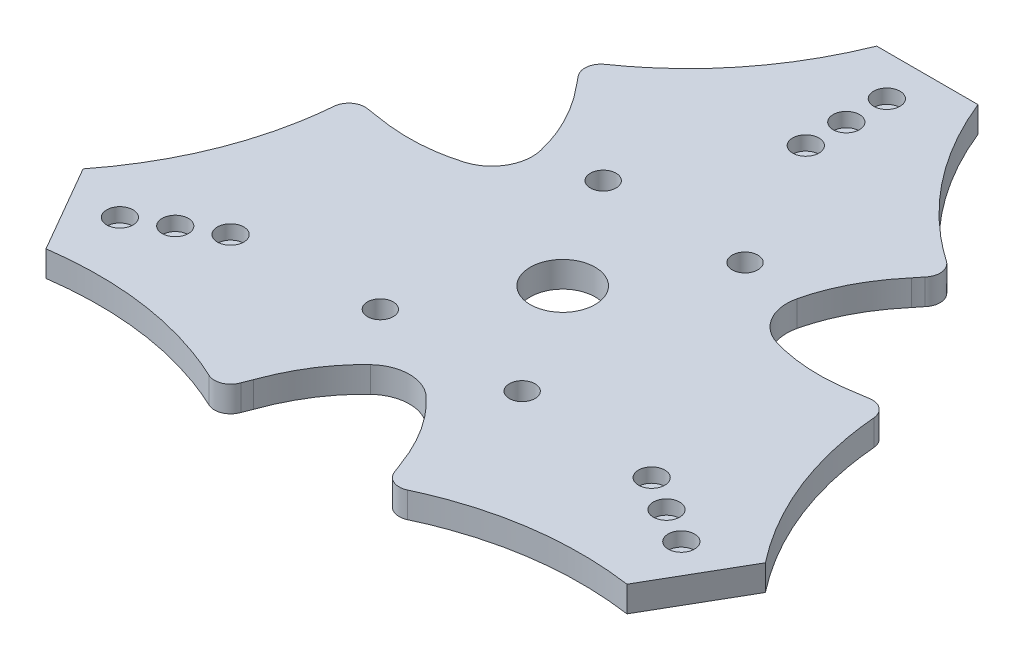
SolidWorks part; units mm, degrees
material "1060 Alloy"
ref_plane "Front Plane" through (0, 0, 0) normal (0, 0, 1) x (1, 0, 0)
ref_plane "Top Plane" through (0, 0, 0) normal (0, 1, 0) x (1, 0, 0)
ref_plane "Right Plane" through (0, 0, 0) normal (1, 0, 0) x (0, 0, -1)
sketch "Croquis2" plane through (0, 0, 0) normal (0, 1, 0) x (1, 0, 0)
  line L0 (168.3846, -68.3494) -> (143.3846, -111.6506)
  line L4 (-25, 180) -> (25, 180)
  line L9 (-143.3846, -111.6506) -> (-168.3846, -68.3494)
  circle A0 centre (0, 0) radius 16
  arc A2 (-84.2408, 105.1778) -> (-85.6392, 93.2818) centre (-79.6723, 98.6105) ccw
  arc A7 (-57.9662, -145.5436) -> (-46.9648, -140.8066) centre (-54.5631, -138.3035) ccw [skipped]
  arc A8 (133.207, 20.3658) -> (123.604, 27.5249) centre (125.2354, 19.693) ccw
  arc A9 (146.0275, 2.5716) -> (136.4245, 9.7306) centre (138.0559, 1.8987) ccw [skipped]
  arc A10 (48.9662, -125.5436) -> (37.9648, -120.8066) centre (45.5631, -118.3035) cw
  arc A11 (84.2408, 105.1778) -> (85.6392, 93.2818) centre (79.6723, 98.6105) cw
  arc A12 (-48.9662, -125.5436) -> (-37.9648, -120.8066) centre (-45.5631, -118.3035) ccw
  arc A13 (-133.207, 20.3658) -> (-123.604, 27.5249) centre (-125.2354, 19.693) cw
  arc A14 (-13.7093, -81.0549) -> (13.7093, -81.0549) centre (0, -95.6171) cw
  arc A15 (-77.0503, 28.6549) -> (-63.341, 52.4001) centre (-82.8068, 47.8085) ccw
  arc A16 (77.0503, 28.6549) -> (63.341, 52.4001) centre (82.8068, 47.8085) cw
  arc A19 (-44.4662, -133.3378) -> (-33.4648, -128.6008) centre (-41.0631, -126.0977) ccw [skipped]
  arc A20 (142.207, 20.3658) -> (132.604, 27.5249) centre (134.2354, 19.693) ccw [skipped]
  spline S0 degree 3 poles (-82.6619, 89.5471) (-72.9001, 78.0045) (-66.4598, 65.6222) (-63.341, 52.4001) knots 0 0 0 0 0.498804 0.498804 0.498804 0.498804
  spline S1 degree 2 poles (85.6392, 93.2818) (84.0859, 91.3724) (82.6619, 89.5471) knots 0 0 0 0.028122 0.028122 0.028122
  spline S2 degree 3 poles (-82.6619, 89.5471) (-83.5706, 90.827) (-84.5599, 92.0732) (-85.6392, 93.2818) knots 0.875207 0.875207 0.875207 0.875207 0.919288 0.919288 0.919288 0.919288
  spline S3 degree 3 poles (-25, 180) (-37.5458, 148.9585) (-57.7553, 123.6025) (-84.2408, 105.1778) knots 0 0 0 0 0.911576 0.911576 0.911576 0.911576
  spline S4 degree 3 poles (25, 180) (37.5458, 148.9585) (57.7553, 123.6025) (84.2408, 105.1778) knots 0 0 0 0 0.911576 0.911576 0.911576 0.911576
  spline S5 degree 3 poles (82.6619, 89.5471) (83.5706, 90.827) (84.5599, 92.0732) (85.6392, 93.2818) knots 0.875207 0.875207 0.875207 0.875207 0.919288 0.919288 0.919288 0.919288
  spline S6 degree 3 poles (82.6619, 89.5471) (72.9001, 78.0045) (66.4598, 65.6222) (63.341, 52.4001) knots 0 0 0 0 0.498804 0.498804 0.498804 0.498804
  spline S7 degree 3 poles (118.881, 26.8137) (104.0039, 24.1311) (90.0604, 24.7448) (77.0503, 28.6549) knots 0 0 0 0 0.498804 0.498804 0.498804 0.498804
  spline S8 degree 2 poles (37.9648, -120.8066) (37.0879, -118.5067) (36.2191, -116.3609) knots 0 0 0 0.028122 0.028122 0.028122
  spline S9 degree 3 poles (118.881, 26.8137) (120.4438, 26.9607) (122.0177, 27.1944) (123.604, 27.5249) knots 0.875207 0.875207 0.875207 0.875207 0.919288 0.919288 0.919288 0.919288
  spline S10 degree 3 poles (168.3846, -68.3494) (147.7748, -41.9636) (135.9205, -11.7837) (133.207, 20.3658) knots 0 0 0 0 0.911576 0.911576 0.911576 0.911576
  spline S11 degree 3 poles (143.3846, -111.6506) (110.229, -106.9949) (78.1653, -111.8188) (48.9662, -125.5436) knots 0 0 0 0 0.911576 0.911576 0.911576 0.911576
  spline S12 degree 2 poles (-85.6392, 93.2818) (-84.0859, 91.3724) (-82.6619, 89.5471) knots 0 0 0 0.028122 0.028122 0.028122
  spline S13 degree 3 poles (36.2191, -116.3608) (36.8732, -117.7877) (37.4578, -119.2676) (37.9648, -120.8066) knots 0.875207 0.875207 0.875207 0.875207 0.919288 0.919288 0.919288 0.919288
  spline S14 degree 3 poles (36.2191, -116.3608) (31.1039, -102.1356) (23.6006, -90.367) (13.7093, -81.0549) knots 0 0 0 0 0.498804 0.498804 0.498804 0.498804
  spline S15 degree 2 poles (123.604, 27.5249) (121.1738, 27.1343) (118.881, 26.8137) knots 0 0 0 0.028122 0.028122 0.028122
  spline S16 degree 3 poles (-36.2191, -116.3608) (-31.1039, -102.1356) (-23.6006, -90.367) (-13.7093, -81.0549) knots 0 0 0 0 0.498804 0.498804 0.498804 0.498804
  spline S17 degree 2 poles (-123.604, 27.5249) (-121.1738, 27.1343) (-118.881, 26.8137) knots 0 0 0 0.028122 0.028122 0.028122
  spline S18 degree 3 poles (-36.2191, -116.3608) (-36.8732, -117.7877) (-37.4578, -119.2676) (-37.9648, -120.8066) knots 0.875207 0.875207 0.875207 0.875207 0.919288 0.919288 0.919288 0.919288
  spline S19 degree 3 poles (-143.3846, -111.6506) (-110.229, -106.9949) (-78.1653, -111.8188) (-48.9662, -125.5436) knots 0 0 0 0 0.911576 0.911576 0.911576 0.911576
  spline S20 degree 3 poles (-168.3846, -68.3494) (-147.7748, -41.9636) (-135.9205, -11.7837) (-133.207, 20.3658) knots 0 0 0 0 0.911576 0.911576 0.911576 0.911576
  spline S21 degree 3 poles (-118.881, 26.8137) (-120.4438, 26.9607) (-122.0177, 27.1944) (-123.604, 27.5249) knots 0.875207 0.875207 0.875207 0.875207 0.919288 0.919288 0.919288 0.919288
  spline S22 degree 3 poles (-118.881, 26.8137) (-104.0039, 24.1311) (-90.0604, 24.7448) (-77.0503, 28.6549) knots 0 0 0 0 0.498804 0.498804 0.498804 0.498804
  spline S23 degree 2 poles (-37.9648, -120.8066) (-37.0879, -118.5067) (-36.2191, -116.3609) knots 0 0 0 0.028122 0.028122 0.028122
  point P0 (0, 180)
  point P3 (-57.9808, 40.4256)
  point P14 (6.0192, -70.4256)
  point P17 (0, 180)
  point P18 (-6.0192, -70.4256)
  point P26 (155.8846, -90)
  point P40 (155.8846, -90)
  point P48 (-155.8846, -90)
  point P61 (-155.8846, -90)
  point P71 (0, 0)
  dimension "D4" = 32
  dimension "D1" = 20
  dimension "D3" = 3
  dimension "D9" = 3
extrude "Delta Base" add sketch "Croquis2" along normal blind 12.7
sketch "Croquis3" plane through (0, 12.7, 0) normal (0, 1, 0) x (1, 0, 0)
  circle A0 centre (0, 120) radius 3
  circle A1 centre (0, 140) radius 3
  circle A2 centre (0, 160) radius 3
  circle A12 centre (103.923, -60) radius 3
  circle A13 centre (121.2436, -70) radius 3
  circle A14 centre (138.5641, -80) radius 3
  circle A15 centre (-103.923, -60) radius 3
  circle A16 centre (-121.2436, -70) radius 3
  circle A17 centre (-138.5641, -80) radius 3
  point P21 (0, 0)
  point P28 (0, 0)
  dimension "D1" = 3
  dimension "D2" = 20
  dimension "D3" = 20
  dimension "D4" = 120
extrude "Cortar-Extruir2" cut sketch "Croquis3" against normal blind 30
sketch "Croquis5" plane through (0, 12.7, 0) normal (0, 1, 0) x (1, 0, 0)
  circle A0 centre (0, 160) radius 6.5
  circle A1 centre (0, 140) radius 6.5
  circle A2 centre (0, 120) radius 6.5
  circle A21 centre (138.5641, -80) radius 6.5
  circle A22 centre (121.2436, -70) radius 6.5
  circle A23 centre (103.923, -60) radius 6.5
  circle A24 centre (-138.5641, -80) radius 6.5
  circle A25 centre (-121.2436, -70) radius 6.5
  circle A26 centre (-103.923, -60) radius 6.5
  point P23 (3.4641, -6)
  point P24 (0, 0)
extrude "Cortar-Extruir3" cut sketch "Croquis5" against normal blind 7
sketch "Croquis6" plane through (0, 12.7, 0) normal (0, 1, 0) x (1, 0, 0)
  circle A0 centre (-35, 55) radius 6.35
  circle A1 centre (35, 55) radius 6.35
  circle A2 centre (-35, -55) radius 6.35
  circle A3 centre (35, -55) radius 6.35
  circle A4 centre (0, 0) radius 16 construction
  point P0 (0, 0)
  dimension "D3" = 55
  dimension "D1" = 110
  dimension "D4" = 55
  dimension "D2" = 70
extrude "Cortar-Extruir4" cut sketch "Croquis6" against normal blind 38
